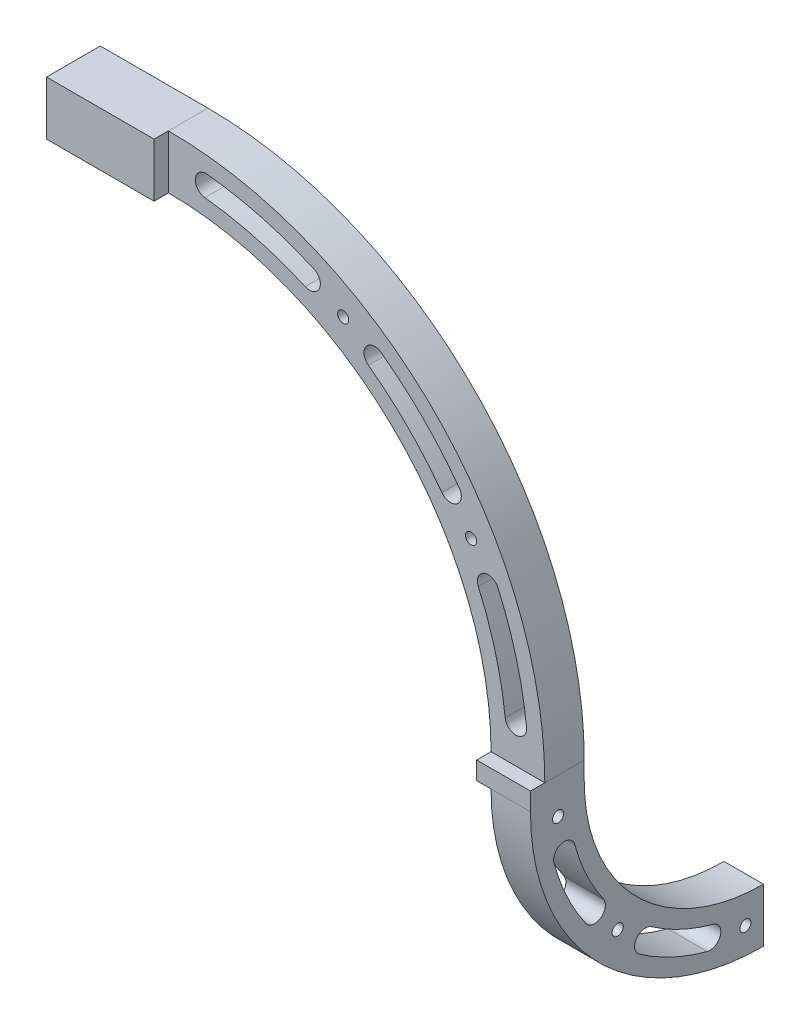
SolidWorks part; units mm, degrees
material "ABS"
ref_plane "前视基准面" through (0, 0, 0) normal (0, 0, 1) x (1, 0, 0)
ref_plane "上视基准面" through (0, 0, 0) normal (0, 1, 0) x (1, 0, 0)
ref_plane "右视基准面" through (0, 0, 0) normal (1, 0, 0) x (0, 0, -1)
other "Configuration Table"
sketch "草图1" plane through (0, 0, 0) normal (0, 0, 1) x (1, 0, 0)
  line L0 (0, 105) -> (0, 0) construction
  line L1 (0, 0) -> (105, 0) construction
  line L2 (90, 0) -> (105, 0)
  line L3 (0, 105) -> (0, 90)
  arc A0 (0, 105) -> (105, 0) centre (0, 0) cw
  arc A1 (0, 90) -> (90, 0) centre (0, 0) cw
  dimension "D1" = 105
  dimension "D2" = 90
extrude "凸台-拉伸1" add sketch "草图1" along normal blind 15
sketch "草图2" plane through (0, 0, 0) normal (0, -1, 0) x (1, 0, 0)
  line L1 (90, 15) -> (105, 15)
  line L2 (90, 15) -> (90, 0)
  line L3 (90, 0) -> (105, 0)
  line L4 (105, 15) -> (105, 0)
extrude "凸台-拉伸2" add sketch "草图2" along normal blind 5
sketch "草图3" plane through (105, 0, 0) normal (1, 0, 0) x (0, 0, -1)
  line L0 (0, -5) -> (50, -5) construction
  line L1 (50, -5) -> (50, -55) construction
  line L2 (50, -55) -> (50, -70)
  line L3 (-15, -5) -> (0, -5)
  arc A0 (0, -5) -> (50, -55) centre (50, -5) ccw
  arc A1 (-15, -5) -> (50, -70) centre (50, -5) ccw
  dimension "D1" = 50
extrude "凸台-拉伸3" add sketch "草图3" against normal blind 15
sketch "草图4" plane through (0, 0, 15) normal (0, 0, 1) x (1, 0, 0)
  line L0 (25.2349, 94.1778) -> (0, 0) construction
  line L1 (0, 0) -> (68.9429, 68.9429) construction
  line L2 (0, 0) -> (94.1778, 25.2349) construction
  line L3 (0, 0) -> (90, 0) construction
  line L4 (48.75, 84.4375) -> (0, 0) construction
  line L5 (84.4375, 48.75) -> (0, 0) construction
  arc A0 (10.4903, 96.934) -> (39.3822, 89.1925) centre (0, 0) cw construction
  arc A1 (40.5939, 91.9368) -> (10.813, 99.9166) centre (0, 0) ccw
  arc A2 (38.1704, 86.4481) -> (10.1675, 93.9514) centre (0, 0) ccw
  arc A3 (38.1704, 86.4481) -> (40.5939, 91.9368) centre (39.3822, 89.1925) ccw
  arc A4 (10.813, 99.9166) -> (10.1675, 93.9514) centre (10.4903, 96.934) ccw
  arc A5 (57.5518, 78.7022) -> (78.7022, 57.5518) centre (0, 0) cw construction
  arc A6 (81.1238, 59.3227) -> (59.3227, 81.1238) centre (0, 0) ccw
  arc A7 (76.2806, 55.781) -> (55.781, 76.2806) centre (0, 0) ccw
  arc A8 (76.2806, 55.781) -> (81.1238, 59.3227) centre (78.7022, 57.5518) ccw
  arc A9 (59.3227, 81.1238) -> (55.781, 76.2806) centre (57.5518, 78.7022) ccw
  arc A10 (89.1925, 39.3822) -> (96.934, 10.4903) centre (0, 0) cw construction
  arc A11 (99.9166, 10.813) -> (91.9368, 40.5939) centre (0, 0) ccw
  arc A12 (93.9514, 10.1675) -> (86.4481, 38.1704) centre (0, 0) ccw
  arc A13 (93.9514, 10.1675) -> (99.9166, 10.813) centre (96.934, 10.4903) ccw
  arc A14 (91.9368, 40.5939) -> (86.4481, 38.1704) centre (89.1925, 39.3822) ccw
  circle A17 centre (84.4375, 48.75) radius 1.55
  circle A18 centre (48.75, 84.4375) radius 1.55
  point P4 (25.2349, 94.1778)
  point P9 (68.9429, 68.9429)
  point P18 (94.1778, 25.2349)
  dimension "D1" = 3
  dimension "D2" = 3
  dimension "D3" = 3
  dimension "D7" = 97.5
  dimension "D8" = 97.5
  dimension "D9" = 97.5
  dimension "D12" = 3.1
  dimension "D13" = 3.1
  dimension "D14" = 15
  dimension "D4" = 15
  dimension "D5" = 45
  dimension "D6" = 75
  dimension "D10" = 97.5
  dimension "D11" = 97.5
  dimension "D15" = 15
  dimension "D16" = 15
  dimension "D17" = 15
  dimension "D18" = 15
sketch "草图5" plane through (105, 0, 0) normal (1, 0, 0) x (0, 0, -1)
  line L0 (-2.1127, -29.3006) -> (50, -5) construction
  line L1 (50, -5) -> (25.6994, -57.1127) construction
  line L2 (50, -55) -> (50, -5) construction
  line L3 (50, -5) -> (0, -5) construction
  line L4 (-7.2812, -10.0115) -> (50, -5) construction
  line L5 (50, -5) -> (9.3414, -45.6586) construction
  line L6 (50, -5) -> (44.9694, -62.5) construction
  arc A0 (-5.5348, -19.9043) -> (2.8856, -37.9618) centre (50, -5) ccw construction
  arc A1 (-8.4322, -20.6819) -> (0.4274, -39.6816) centre (50, -5) ccw
  arc A2 (-2.6373, -19.1267) -> (5.3437, -36.2421) centre (50, -5) ccw
  arc A3 (-2.6373, -19.1267) -> (-8.4322, -20.6819) centre (-5.5348, -19.9043) ccw
  arc A4 (0.4274, -39.6816) -> (5.3437, -36.2421) centre (2.8856, -37.9618) ccw
  arc A5 (17.0382, -52.1144) -> (35.0957, -60.5348) centre (50, -5) ccw construction
  arc A6 (15.3184, -54.5726) -> (34.3181, -63.4322) centre (50, -5) ccw
  arc A7 (18.7579, -49.6563) -> (35.8733, -57.6373) centre (50, -5) ccw
  arc A8 (18.7579, -49.6563) -> (15.3184, -54.5726) centre (17.0382, -52.1144) ccw
  arc A9 (34.3181, -63.4322) -> (35.8733, -57.6373) centre (35.0957, -60.5348) ccw
  circle A13 centre (44.9694, -62.5) radius 1.55
  circle A14 centre (9.3414, -45.6586) radius 1.55
  circle A15 centre (-7.2812, -10.0115) radius 1.55
  point P4 (-2.1127, -29.3006)
  point P9 (25.6994, -57.1127)
  point P28 (27.1678, -57.7725)
  point P31 (-2.4634, -28.5339)
  dimension "D1" = 57.5
  dimension "D2" = 57.5
  dimension "D8" = 3.1
  dimension "D9" = 3.1
  dimension "D10" = 3.1
  dimension "D12" = 25
  dimension "D13" = 3
  dimension "D16" = 3
  dimension "D3" = 57.5
  dimension "D4" = 57.5
  dimension "D5" = 57.5
  dimension "D6" = 10
  dimension "D7" = 10
  dimension "D11" = 45
  dimension "D14" = 5
  dimension "D15" = 5
  dimension "D17" = 25
extrude "切除-拉伸1" cut sketch "草图4" against normal through all
extrude "切除-拉伸2" cut sketch "草图5" against normal through all
sketch "草图6" plane through (105, 0, 0) normal (1, 0, 0) x (0, 0, -1)
  line L0 (50, -55) -> (50, -70)
  line L1 (0, -5) -> (-15, -5)
  arc A0 (0, -5) -> (50, -55) centre (50, -5) ccw
  arc A1 (-15, -5) -> (50, -70) centre (50, -5) ccw
extrude "切除-拉伸3" [suppressed] cut sketch "草图6" against normal blind 4
sketch "草图7" plane through (0, 0, 15) normal (0, 0, 1) x (1, 0, 0)
  line L0 (0, 105) -> (0, 90)
  line L1 (90, 0) -> (105, 0)
  line L2 (90, -5) -> (90, 0) construction
  arc A0 (0, 90) -> (90, 0) centre (0, 0) cw
  arc A1 (0, 105) -> (105, 0) centre (0, 0) cw
extrude "切除-拉伸4" cut sketch "草图7" against normal blind 4
sketch "草图8" plane through (90, 0, 0) normal (-1, 0, 0) x (0, 0, 1)
  line L0 (-50, -55) -> (-50, -70)
  line L1 (0, -5) -> (15, -5)
  arc A0 (-50, -55) -> (0, -5) centre (-50, -5) ccw
  arc A1 (-50, -55) -> (0, -5) centre (-50, -5) ccw construction
  arc A2 (-50, -70) -> (15, -5) centre (-50, -5) ccw
extrude "切除-拉伸5" cut sketch "草图8" against normal blind 4
sketch "草图9" plane through (0, 0, 0) normal (-1, 0, 0) x (0, 0, 1)
  line L1 (0, 105) -> (15, 105)
  line L2 (0, 105) -> (0, 90)
  line L3 (0, 90) -> (15, 90)
  line L4 (15, 105) -> (15, 90)
  point P5 (0, 90)
  dimension "D1" = 15
extrude "凸台-拉伸4" add sketch "草图9" along normal blind 30
